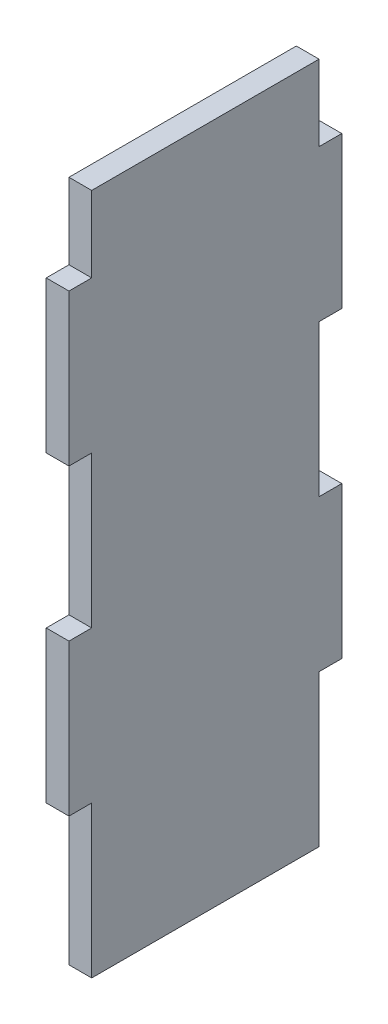
SolidWorks part; units mm, degrees
material "Acrilico TEC"
ref_plane "Front Plane" through (0, 0, 0) normal (0, 0, 1) x (1, 0, 0)
ref_plane "Top Plane" through (0, 0, 0) normal (0, 1, 0) x (1, 0, 0)
ref_plane "Right Plane" through (0, 0, 0) normal (1, 0, 0) x (0, 0, -1)
sketch "Sketch1" plane through (0, 0, 0) normal (1, 0, 0) x (0, 0, -1)
  line L0 (-15, 0) -> (15, 0)
  line L1 (15, 0) -> (15, 20)
  line L2 (15, 20) -> (18, 20)
  line L3 (18, 20) -> (18, 40)
  line L4 (18, 40) -> (15, 40)
  line L5 (15, 40) -> (15, 60)
  line L6 (15, 60) -> (18, 60)
  line L7 (18, 60) -> (18, 80)
  line L8 (18, 80) -> (15, 80)
  line L9 (15, 80) -> (15, 90)
  line L10 (15, 90) -> (-15, 90)
  line L11 (0, 90) -> (0, 0) construction
  line L12 (-15, 80) -> (-15, 90)
  line L13 (-18, 80) -> (-15, 80)
  line L14 (-18, 60) -> (-18, 80)
  line L15 (-15, 60) -> (-18, 60)
  line L16 (-15, 40) -> (-15, 60)
  line L17 (-18, 40) -> (-15, 40)
  line L18 (-18, 20) -> (-18, 40)
  line L19 (-15, 20) -> (-18, 20)
  line L20 (-15, 0) -> (-15, 20)
  dimension "D1" = 15
  dimension "D2" = 20
  dimension "D3" = 20
  dimension "D4" = 20
  dimension "D5" = 20
  dimension "D6" = 10
  dimension "D7" = 3
extrude "Boss-Extrude1" add sketch "Sketch1" along normal blind 3
